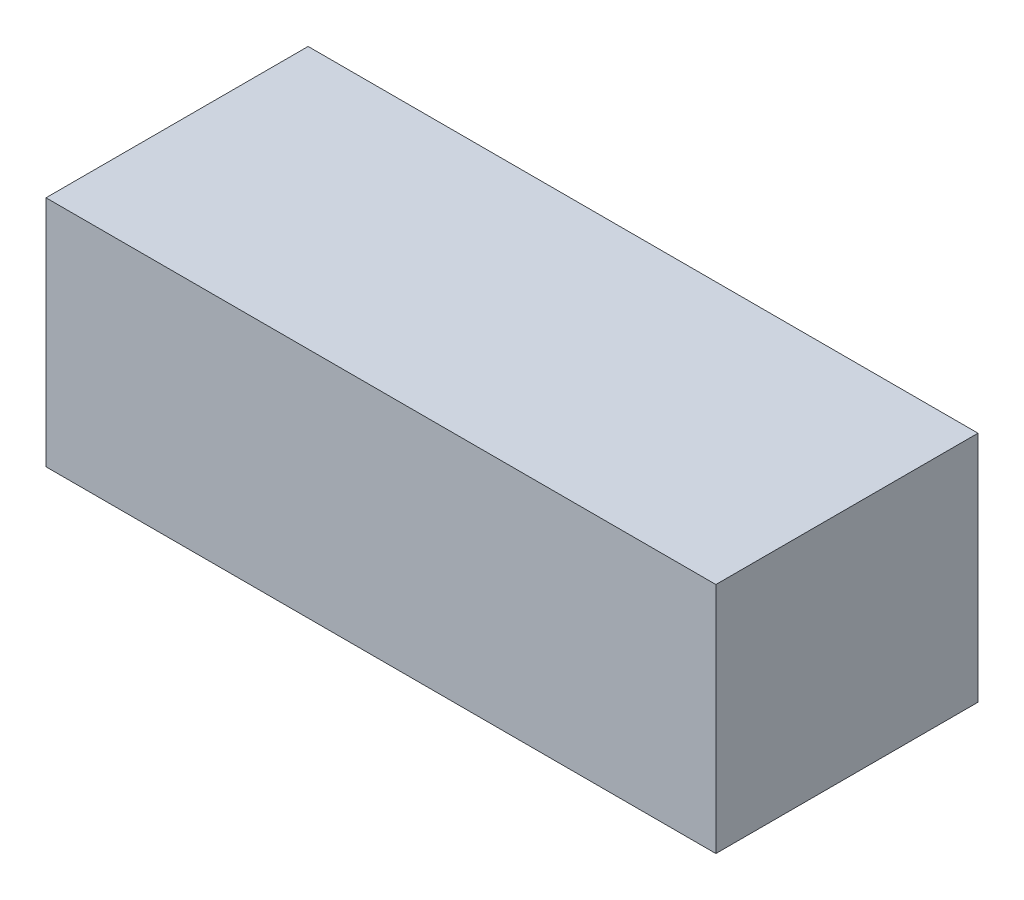
SolidWorks part; units mm, degrees
ref_plane "前视基准面" through (0, 0, 0) normal (0, 0, 1) x (1, 0, 0)
ref_plane "上视基准面" through (0, 0, 0) normal (0, 1, 0) x (1, 0, 0)
ref_plane "右视基准面" through (0, 0, 0) normal (1, 0, 0) x (0, 0, -1)
other "Configuration Table"
sketch "草图1" plane through (0, 0, 0) normal (0, 1, 0) x (1, 0, 0)
  line L0 (0, 9) -> (0, -9) construction
  line L1 (-23, 9) -> (23, 9)
  line L2 (-23, 9) -> (-23, -9)
  line L3 (-23, -9) -> (23, -9)
  line L4 (23, 9) -> (23, -9)
  line L6 (-23, 0) -> (23, 0) construction
  dimension "D1" = 46
  dimension "D2" = 18
extrude "凸台-拉伸1" add sketch "草图1" along normal blind 16
